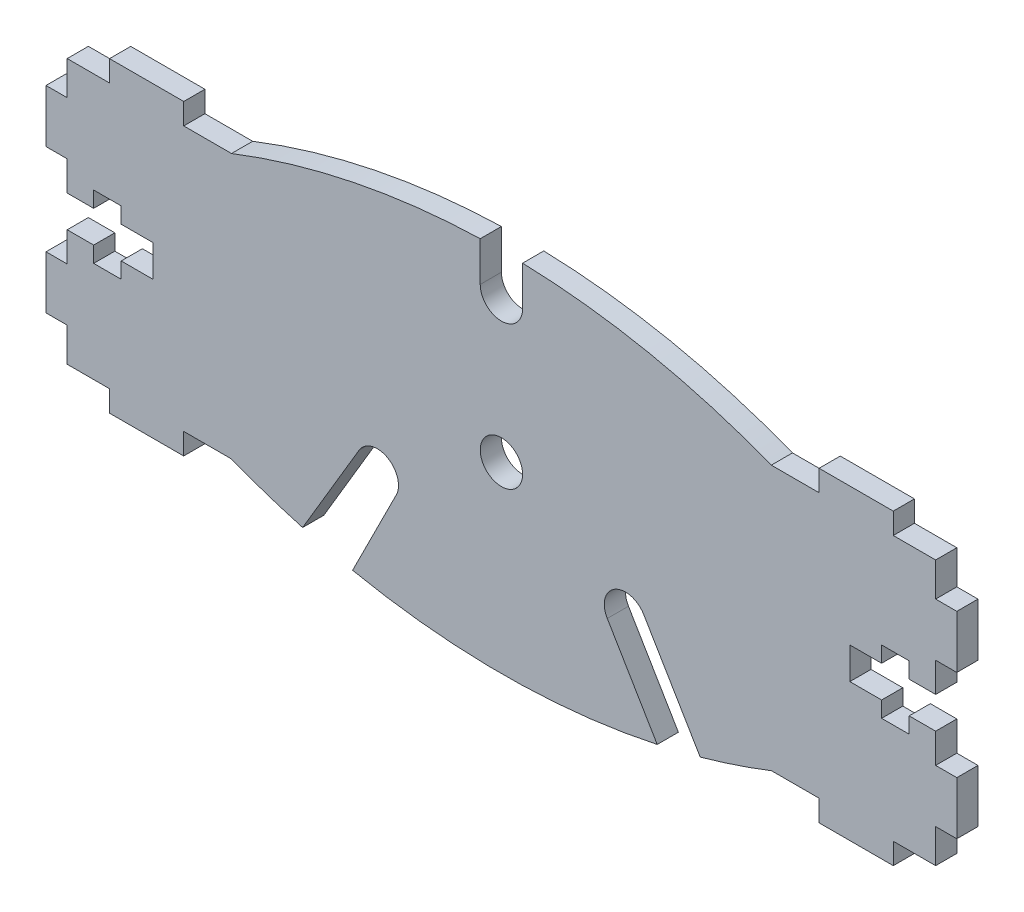
SolidWorks part; units mm, degrees
ref_plane "前视基准面" through (0, 0, 0) normal (0, 0, 1) x (1, 0, 0)
ref_plane "上视基准面" through (0, 0, 0) normal (0, 1, 0) x (1, 0, 0)
ref_plane "右视基准面" through (0, 0, 0) normal (1, 0, 0) x (0, 0, -1)
sketch "草图1" plane through (0, 0, 0) normal (0, 0, 1) x (1, 0, 0)
  line L205 (-29.9944, 12.4944) -> (-25.4834, 12.4944)
  line L238 (-30, -12.4856) -> (-25.5033, -12.4856)
  line L376 (-37, 14.4944) -> (-29.9944, 14.4944)
  line L378 (-29.9944, 12.4944) -> (-29.9944, 14.4944)
  line L379 (-37, 14.4944) -> (-37, 12.5)
  line L380 (-37, 12.5) -> (-41, 12.5)
  line L381 (-37, -12.5) -> (-41, -12.5)
  line L382 (-37, -14.5) -> (-37, -12.5)
  line L383 (-30, -12.4856) -> (-30, -14.5)
  line L385 (-37, -14.5) -> (-30, -14.5)
  line L399 (0, 0) -> (0, -2.02) construction
  line L405 (-38.5, -1.5) -> (-41, -1.5)
  line L406 (-38.5, 1.5) -> (-41, 1.5)
  line L407 (-38.5, -1.5) -> (-38.5, -3)
  line L408 (-32.9, 1.5) -> (-32.9, -1.5)
  line L409 (-38.5, 1.5) -> (-38.5, 3)
  line L410 (-38.5, -3) -> (-35.9, -3)
  line L411 (-35.9, -3) -> (-35.9, -1.5)
  line L412 (-35.9, -1.5) -> (-32.9, -1.5)
  line L413 (-35.9, 1.5) -> (-32.9, 1.5)
  line L414 (-35.9, 3) -> (-35.9, 1.5)
  line L415 (-38.5, 3) -> (-35.9, 3)
  line L430 (-41, 12.5) -> (-41, 9.3)
  line L431 (-41, 9.3) -> (-43, 9.3)
  line L432 (-43, 9.3) -> (-43, 4.3)
  line L433 (-43, 4.3) -> (-41, 4.3)
  line L434 (-41, 4.3) -> (-41, 1.5)
  line L435 (0, 0) -> (-3.6686, 0) construction
  line L436 (-41, -4.3) -> (-41, -1.5)
  line L437 (-41, -12.5) -> (-41, -9.3)
  line L438 (-43, -4.3) -> (-41, -4.3)
  line L439 (-43, -9.3) -> (-43, -4.3)
  line L440 (-41, -9.3) -> (-43, -9.3)
  line L441 (29.9944, 12.4944) -> (25.4834, 12.4944)
  line L442 (41, -9.3) -> (43, -9.3)
  line L443 (43, -9.3) -> (43, -4.3)
  line L444 (43, -4.3) -> (41, -4.3)
  line L445 (41, -12.5) -> (41, -9.3)
  line L446 (41, -4.3) -> (41, -1.5)
  line L447 (41, 4.3) -> (41, 1.5)
  line L448 (43, 4.3) -> (41, 4.3)
  line L449 (43, 9.3) -> (43, 4.3)
  line L450 (41, 9.3) -> (43, 9.3)
  line L451 (41, 12.5) -> (41, 9.3)
  line L452 (38.5, 3) -> (35.9, 3)
  line L453 (35.9, 3) -> (35.9, 1.5)
  line L454 (35.9, 1.5) -> (32.9, 1.5)
  line L455 (35.9, -1.5) -> (32.9, -1.5)
  line L456 (35.9, -3) -> (35.9, -1.5)
  line L457 (38.5, -3) -> (35.9, -3)
  line L458 (38.5, 1.5) -> (38.5, 3)
  line L459 (32.9, 1.5) -> (32.9, -1.5)
  line L460 (38.5, -1.5) -> (38.5, -3)
  line L461 (38.5, 1.5) -> (41, 1.5)
  line L462 (38.5, -1.5) -> (41, -1.5)
  line L463 (37, -14.5) -> (30, -14.5)
  line L464 (30, -12.4856) -> (30, -14.5)
  line L465 (37, -14.5) -> (37, -12.5)
  line L466 (37, -12.5) -> (41, -12.5)
  line L467 (37, 12.5) -> (41, 12.5)
  line L468 (37, 14.4944) -> (37, 12.5)
  line L469 (29.9944, 12.4944) -> (29.9944, 14.4944)
  line L470 (37, 14.4944) -> (29.9944, 14.4944)
  line L471 (30, -12.4856) -> (25.5033, -12.4856)
  line L472 (2, 13.53) -> (2, 22.9978) construction
  line L473 (-2, 13.53) -> (-2, 22.9978) construction
  line L474 (-11.7173, -6.765) -> (-18.3899, -18.0141) construction
  line L475 (-11.7173, -6.765) -> (-8.0181, -8.9593) construction
  line L476 (-11.7173, -6.765) -> (-15.254, -4.6671) construction
  line L478 (-13.4375, -5.7447) -> (-20.0834, -16.9489) construction
  line L479 (11.7173, -6.765) -> (18.3899, -18.0141) construction
  line L480 (9.3608, -8.1628) -> (15.2828, -4.6501) construction
  line L481 (9.9972, -7.7853) -> (16.6431, -18.9895) construction
  line L482 (13.4375, -5.7447) -> (20.0834, -16.9489) construction
  line L483 (-2, 13.53) -> (-2, 17.2693)
  line L484 (2, 13.53) -> (2, 17.2693)
  line L485 (-18.7693, -14.7335) -> (-13.4375, -5.7447)
  line L487 (9.9972, -7.7853) -> (14.7117, -15.7334)
  line L488 (18.7693, -14.7335) -> (13.4375, -5.7447)
  line L489 (-9.9972, -7.7853) -> (-14.0519, -15.8719)
  circle A13 centre (0, 0) radius 15 construction
  circle A14 centre (0, 0) radius 13.53 construction
  circle A15 centre (-15, 0) radius 1.65 construction
  circle A16 centre (-7.5, 12.9904) radius 1.65 construction
  circle A17 centre (7.5, 12.9904) radius 1.65 construction
  circle A18 centre (15, 0) radius 1.65 construction
  circle A19 centre (7.5, -12.9904) radius 1.65 construction
  circle A20 centre (-7.5, -12.9904) radius 1.65 construction
  circle A21 centre (0, 13.53) radius 2 construction
  circle A22 centre (11.7173, -6.765) radius 2 construction
  circle A23 centre (-11.7173, -6.765) radius 2 construction
  circle A24 centre (0, 0) radius 2
  arc A27 (-2, 13.53) -> (2, 13.53) centre (0, 13.53) ccw
  arc A30 (9.9972, -7.7853) -> (13.4375, -5.7447) centre (11.7173, -6.765) cw
  arc A35 (-25.4834, 12.4944) -> (25.4834, 12.4944) centre (0, -52.7022) cw construction
  arc A36 (-25.5033, -12.4856) -> (25.5033, -12.4856) centre (0, 52.7032) ccw construction
  arc A37 (-25.4834, 12.4944) -> (-2, 17.2693) centre (0, -52.7022) cw
  arc A38 (2, 17.2693) -> (25.4834, 12.4944) centre (0, -52.7022) cw
  arc A39 (-25.5033, -12.4856) -> (-18.7693, -14.7335) centre (0, 52.7032) ccw
  arc A40 (-14.0519, -15.8719) -> (14.7117, -15.7334) centre (0, 52.7032) ccw
  arc A41 (25.5033, -12.4856) -> (18.7693, -14.7335) centre (0, 52.7032) cw
  arc A42 (-13.4375, -5.7447) -> (-9.9972, -7.7853) centre (-11.7173, -6.765) cw
  dimension "D1" = 6
  dimension "D2" = 3
extrude "凸台-拉伸2" add sketch "草图1" along normal blind 2
sketch "草图2" plane through (-41, 0, 0) normal (-1, 0, 0) x (0, 0, 1)
  line L0 (2, 1.5) -> (0, -1.5) construction
  circle A0 centre (1, 0) radius 1.5
sketch "草图3" plane through (41, 0, 0) normal (1, 0, 0) x (0, 0, -1)
  line L0 (-2, -1.5) -> (0, 1.5) construction
  circle A0 centre (-1, 0) radius 1.5
